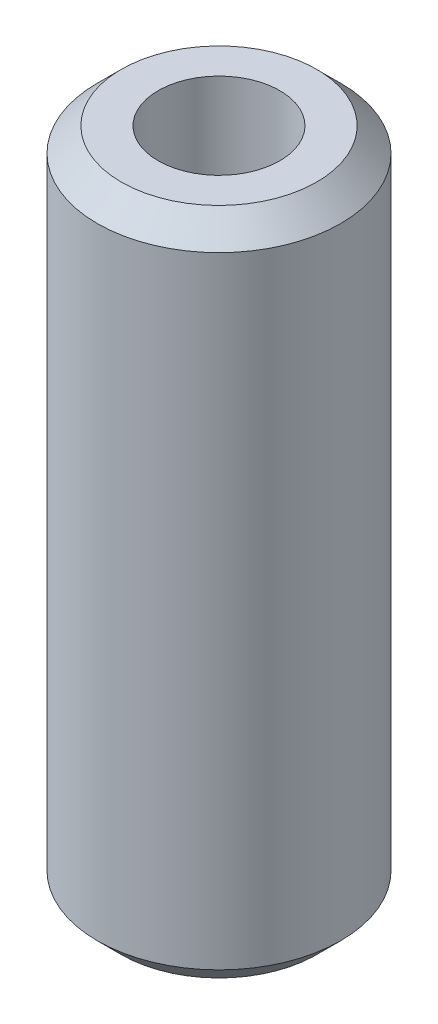
SolidWorks part; units mm, degrees
material "Brass"
ref_plane "Front Plane" through (0, 0, 0) normal (0, 0, 1) x (1, 0, 0)
ref_plane "Top Plane" through (0, 0, 0) normal (0, 1, 0) x (1, 0, 0)
ref_plane "Right Plane" through (0, 0, 0) normal (1, 0, 0) x (0, 0, -1)
sketch "Sketch1" plane through (0, 0, 0) normal (0, 1, 0) x (1, 0, 0)
  circle A0 centre (0, 0) radius 6.35
  circle A1 centre (0, 0) radius 12.7
  dimension "D1" = 25.4
  dimension "D2" = 12.7
extrude "Boss-Extrude1" add sketch "Sketch1" along normal mid plane 69.85
chamfer "Chamfer1" distance 2.5 angle 45 2 edges at (0, -34.925, 12.7) (0, 34.925, 12.7)
